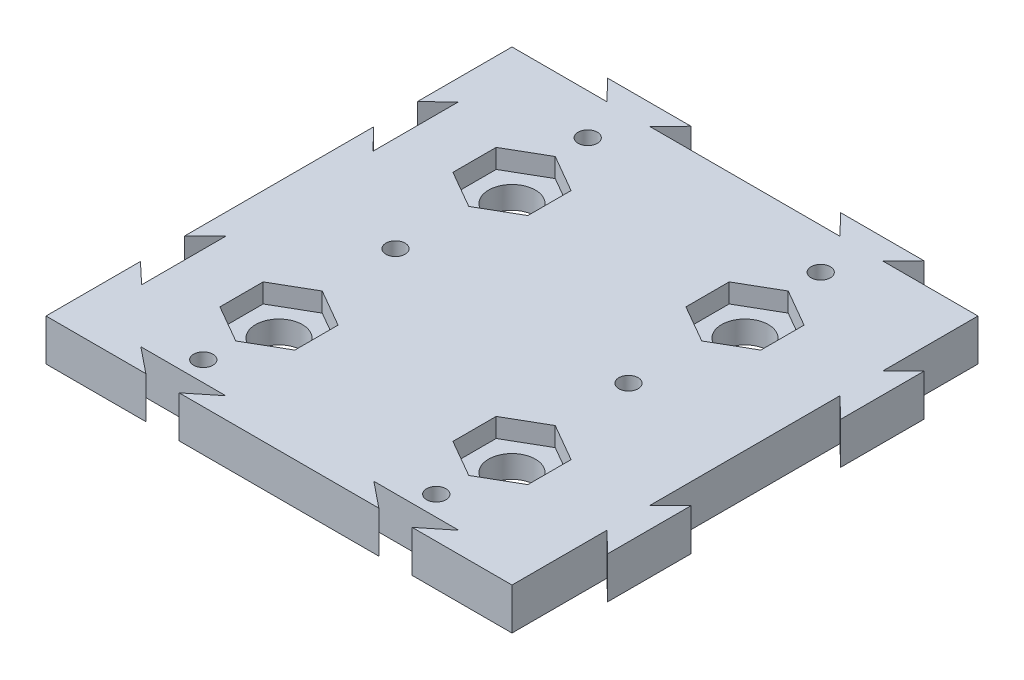
SolidWorks part; units mm, degrees
ref_plane "Front Plane" through (0, 0, 0) normal (0, 0, 1) x (1, 0, 0)
ref_plane "Top Plane" through (0, 0, 0) normal (0, 1, 0) x (1, 0, 0)
ref_plane "Right Plane" through (0, 0, 0) normal (1, 0, 0) x (0, 0, -1)
sketch "Sketch1" plane through (0, 0, 0) normal (0, 1, 0) x (1, 0, 0)
  line L1 (-17.78, -17.78) -> (17.78, -17.78)
  line L2 (-17.78, -17.78) -> (-17.78, 17.78)
  line L3 (-17.78, 17.78) -> (17.78, 17.78)
  line L4 (17.78, -17.78) -> (17.78, 17.78)
  line L5 (-17.78, -17.78) -> (17.78, 17.78) construction
  line L6 (-17.78, 17.78) -> (17.78, -17.78) construction
  point P0 (0, 0)
  dimension "D1" = 35.56
  dimension "D2" = 35.56
extrude "Boss-Extrude1" add sketch "Sketch1" along normal blind 6.35
sketch "Sketch2" plane through (0, 6.35, 0) normal (0, 1, 0) x (1, 0, 0)
  line L1 (0, 6.5991) -> (-5.715, 3.2996)
  line L2 (-5.715, 3.2996) -> (-5.715, -3.2996)
  line L3 (-5.715, -3.2996) -> (0, -6.5991)
  line L4 (0, -6.5991) -> (5.715, -3.2996)
  line L5 (5.715, -3.2996) -> (5.715, 3.2996)
  line L6 (5.715, 3.2996) -> (0, 6.5991)
  circle A0 centre (0, 0) radius 5.715 construction
  dimension "D1" = 11.43
extrude "Cut-Extrude1" cut sketch "Sketch2" against normal blind 2.921
hole_wizard "1/4 Clearance Hole1" positions "Sketch4" profile "Sketch3" hole size "1/4" standard "ANSI Inch"
sketch "Sketch4" plane through (0, 3.429, 0) normal (0, 1, 0) x (1, 0, 0)
  point P0 (0, 0)
sketch "Sketch3" plane through (0, 3.429, 0) normal (1, 0, 0) x (0, 0, 1)
  line L0 (0, 0) -> (0, 11.0358)
  line L1 (0, 11.0358) -> (3.5712, 8.89)
  line L2 (3.5712, 8.89) -> (3.5712, 0)
  line L5 (3.5712, 0) -> (0, 0)
  line L10 (0, 11.0358) -> (-3.5712, 8.89) construction
  line L11 (0, -6.35) -> (0, 107.95) construction
  dimension "Hole Dia." = 7.1425
  dimension "Hole Depth" = 8.89
  dimension "Drill Angle" = 118
pattern_linear "LPattern11" count 2 spacing 35.56 along (0, 0, 1) count 2 spacing 35.56 along (-1, 0, 0) of "Boss-Extrude1", "Cut-Extrude1", "1/4 Clearance Hole1"
hole_wizard "CBORE for #4 Socket Head Cap Screw5" positions "Sketch16" profile "Sketch15" counterbore size "#4" standard "ANSI Inch"
sketch "Sketch16" plane through (0, 0, 0) normal (0, -1, 0) x (-1, 0, 0)
  point P0 (0, 11.557)
  dimension "D1" = 11.557
sketch "Sketch15" plane through (0, 0, -11.557) normal (1, 0, 0) x (0, 0, -1)
  line L0 (0, 0) -> (0, 9.7752)
  line L1 (0, 9.7752) -> (1.4732, 8.89)
  line L2 (1.4732, 8.89) -> (1.4732, 3.81)
  line L3 (1.4732, 3.81) -> (2.794, 3.81)
  line L4 (2.794, 3.81) -> (2.794, 0)
  line L5 (2.794, 0) -> (0, 0)
  line L10 (0, 9.7752) -> (-1.4732, 8.89) construction
  line L11 (0, -6.35) -> (0, 107.95) construction
  dimension "Hole Dia." = 2.9464
  dimension "Hole Depth" = 8.89
  dimension "C'Bore Dia." = 5.588
  dimension "C'Bore Depth" = 3.81
  dimension "Drill Angle" = 118
pattern_linear "LPattern15" count 2 spacing 35.56 along (-1, 0, 0) of "CBORE for #4 Socket Head Cap Screw5"
hole_wizard "CBORE for #4 Socket Head Cap Screw6" positions "Sketch18" profile "Sketch17" counterbore size "#4" standard "ANSI Inch"
sketch "Sketch18" plane through (0, 0, 0) normal (0, -1, 0) x (-1, 0, 0)
  point P0 (0, -17.78)
  dimension "D1" = 17.78
sketch "Sketch17" plane through (0, 0, 17.78) normal (1, 0, 0) x (0, 0, -1)
  line L0 (0, 0) -> (0, 9.7752)
  line L1 (0, 9.7752) -> (1.4732, 8.89)
  line L2 (1.4732, 8.89) -> (1.4732, 3.81)
  line L3 (1.4732, 3.81) -> (2.794, 3.81)
  line L4 (2.794, 3.81) -> (2.794, 0)
  line L5 (2.794, 0) -> (0, 0)
  line L10 (0, 9.7752) -> (-1.4732, 8.89) construction
  line L11 (0, -6.35) -> (0, 107.95) construction
  dimension "Hole Dia." = 2.9464
  dimension "Hole Depth" = 8.89
  dimension "C'Bore Dia." = 5.588
  dimension "C'Bore Depth" = 3.81
  dimension "Drill Angle" = 118
pattern_linear "LPattern16" count 2 spacing 35.56 along (-1, 0, 0) of "CBORE for #4 Socket Head Cap Screw6"
ref_plane "Plane1" through (0, 0, 17.78) normal (0, 0, 1) x (1, 0, 0)
mirror "Mirror1" about plane through (0, 0, 17.78) normal (0, 0, 1) of "LPattern15", "CBORE for #4 Socket Head Cap Screw5"
sketch "Sketch20" plane through (0, 0, 0) normal (0, 1, 0) x (1, 0, 0)
  line L1 (17.78, -53.34) -> (17.78, 17.78) construction
  line L2 (17.78, 6.35) -> (20.955, 6.35)
  line L3 (17.78, 6.35) -> (17.78, -6.35)
  line L4 (17.78, -6.35) -> (20.955, -6.35)
  line L5 (20.955, 6.35) -> (20.955, -6.35)
  line L7 (17.78, -29.21) -> (20.955, -29.21)
  line L8 (17.78, -29.21) -> (17.78, -41.91)
  line L9 (17.78, -41.91) -> (20.955, -41.91)
  line L10 (20.955, -29.21) -> (20.955, -41.91)
  dimension "D1" = 6.35
  dimension "D2" = 12.7
  dimension "D3" = 3.175
  dimension ".125" = 3.175
  dimension "D5" = 12.7
  dimension "D6" = 6.35
extrude "Boss-Extrude2" add sketch "Sketch20" along normal up to surface (6.35 mm away) up to face at (-35.56, 6.35, 45.6438)
sketch "Sketch21" plane through (0, 6.35, 0) normal (0, 1, 0) x (1, 0, 0)
  line L0 (20.955, -6.35) -> (17.78, -6.35)
  line L1 (17.78, -6.35) -> (17.78, -3.302)
  line L2 (17.78, -3.302) -> (20.955, -6.35)
  line L3 (20.955, 6.35) -> (17.78, 6.35)
  line L4 (17.78, 6.35) -> (17.78, 3.302)
  line L5 (17.78, 3.302) -> (20.955, 6.35)
  line L6 (20.955, -29.21) -> (17.78, -29.21)
  line L7 (17.78, -29.21) -> (17.78, -32.258)
  line L8 (17.78, -32.258) -> (20.955, -29.21)
  line L9 (20.955, -41.91) -> (17.78, -41.91)
  line L10 (17.78, -41.91) -> (17.78, -38.862)
  line L11 (17.78, -38.862) -> (20.955, -41.91)
  dimension "D1" = 3.048
  dimension "D2" = 3.048
  dimension "D3" = 3.048
  dimension "D4" = 3.048
extrude "Cut-Extrude2" cut sketch "Sketch21" against normal through all
sketch "Sketch22" plane through (0, 0, 0) normal (0, 1, 0) x (1, 0, 0)
  line L0 (-53.34, -53.34) -> (17.78, -53.34) construction
  line L1 (-41.91, -53.34) -> (-29.21, -53.34)
  line L2 (-41.91, -53.34) -> (-41.91, -56.515)
  line L3 (-41.91, -56.515) -> (-29.21, -56.515)
  line L4 (-29.21, -53.34) -> (-29.21, -56.515)
  line L6 (-6.35, -53.34) -> (6.35, -53.34)
  line L7 (-6.35, -53.34) -> (-6.35, -56.515)
  line L8 (-6.35, -56.515) -> (6.35, -56.515)
  line L9 (6.35, -53.34) -> (6.35, -56.515)
  dimension "D1" = 12.7
  dimension "D2" = 12.7
  dimension "D3" = 6.35
  dimension "D4" = 6.35
  dimension "D5" = 3.175
  dimension "D6" = 3.175
extrude "Boss-Extrude3" add sketch "Sketch22" along normal up to surface (6.35 mm away) up to face at (-35.56, 6.35, 45.6438)
sketch "Sketch23" plane through (0, 6.35, 0) normal (0, 1, 0) x (1, 0, 0)
  line L0 (-41.91, -56.515) -> (-41.91, -53.34)
  line L1 (-41.91, -53.34) -> (-38.862, -53.34)
  line L2 (-38.862, -53.34) -> (-41.91, -56.515)
  line L3 (-29.21, -56.515) -> (-29.21, -53.34)
  line L4 (-29.21, -53.34) -> (-32.258, -53.34)
  line L5 (-32.258, -53.34) -> (-29.21, -56.515)
  line L6 (-6.35, -56.515) -> (-6.35, -53.34)
  line L7 (-6.35, -53.34) -> (-3.302, -53.34)
  line L8 (-3.302, -53.34) -> (-6.35, -56.515)
  line L9 (6.35, -56.515) -> (6.35, -53.34)
  line L10 (6.35, -53.34) -> (3.302, -53.34)
  line L11 (3.302, -53.34) -> (6.35, -56.515)
  dimension "D1" = 3.048
  dimension "D2" = 3.048
  dimension "D3" = 3.048
  dimension "D4" = 3.048
extrude "Cut-Extrude3" cut sketch "Sketch23" against normal through all
sketch "Sketch24" plane through (0, 6.35, 0) normal (0, 1, 0) x (1, 0, 0)
  line L0 (-53.34, 3.3655) -> (-53.34, -3.3655)
  line L2 (-53.34, 17.78) -> (-53.34, -53.34) construction
  line L3 (-53.34, -3.3655) -> (-50.165, -6.5913)
  line L4 (-50.165, -6.5913) -> (-50.165, 6.3627)
  line L5 (-50.165, 6.3627) -> (-53.34, 3.3655)
  dimension "D1" = 12.954
  dimension "D2" = 6.3627
  dimension "D3" = 3.175
  dimension "D4" = 6.731
  dimension "D5" = 3.3655
extrude "Cut-Extrude4" cut sketch "Sketch24" against normal through all
mirror "Mirror2" about plane through (0, 0, 17.78) normal (0, 0, 1) of "Cut-Extrude4"
sketch "Sketch25" plane through (0, 6.35, 0) normal (0, 1, 0) x (1, 0, 0)
  line L0 (-38.1, 17.78) -> (-33.02, 17.78)
  line L1 (17.78, 17.78) -> (-53.34, 17.78) construction
  line L2 (-33.02, 17.78) -> (-29.083, 14.605)
  line L3 (-29.083, 14.605) -> (-42.037, 14.605)
  line L4 (-42.037, 14.605) -> (-38.1, 17.78)
  line L5 (-2.54, 17.78) -> (2.54, 17.78)
  line L6 (2.54, 17.78) -> (6.477, 14.605)
  line L7 (6.477, 14.605) -> (-6.477, 14.605)
  line L8 (-6.477, 14.605) -> (-2.54, 17.78)
  dimension "D1" = 3.175
  dimension "D2" = 5.08
  dimension "D3" = 12.954
  dimension "D4" = 6.477
  dimension "D5" = 2.54
  dimension "D6" = 12.954
  dimension "D7" = 5.08
  dimension "D8" = 2.54
  dimension "D9" = 3.175
extrude "Cut-Extrude5" cut sketch "Sketch25" against normal through all
mirror "Mirror3" about plane through (0, 0, 17.78) normal (0, 0, 1) of "Cut-Extrude5", "Cut-Extrude3", "Boss-Extrude3"
sketch "Sketch26" plane through (0, 6.35, 0) normal (0, 1, 0) x (1, 0, 0)
  line L0 (-29.083, 14.605) -> (-33.02, 17.78)
  line L1 (-42.037, 14.605) -> (-29.083, 14.605)
  line L2 (-33.02, 17.78) -> (-38.1, 17.78)
  line L3 (-38.1, 17.78) -> (-42.037, 14.605)
  line L4 (-6.477, 14.605) -> (6.477, 14.605)
  line L5 (6.477, 14.605) -> (2.54, 17.78)
  line L6 (2.54, 17.78) -> (-2.54, 17.78)
  line L7 (-2.54, 17.78) -> (-6.477, 14.605)
extrude "Boss-Extrude4" add sketch "Sketch26" against normal up to surface (6.35 mm away) up to face at (-35.56, 0, 51.7525)
sketch "Sketch27" plane through (0, 6.35, 0) normal (0, 1, 0) x (1, 0, 0)
  line L1 (-53.34, -53.34) -> (17.78, -53.34)
  line L2 (-53.34, -53.34) -> (-53.34, -60.1425)
  line L3 (-53.34, -60.1425) -> (17.78, -60.1425)
  line L4 (17.78, -53.34) -> (17.78, -60.1425)
extrude "Cut-Extrude6" cut sketch "Sketch27" against normal through all
